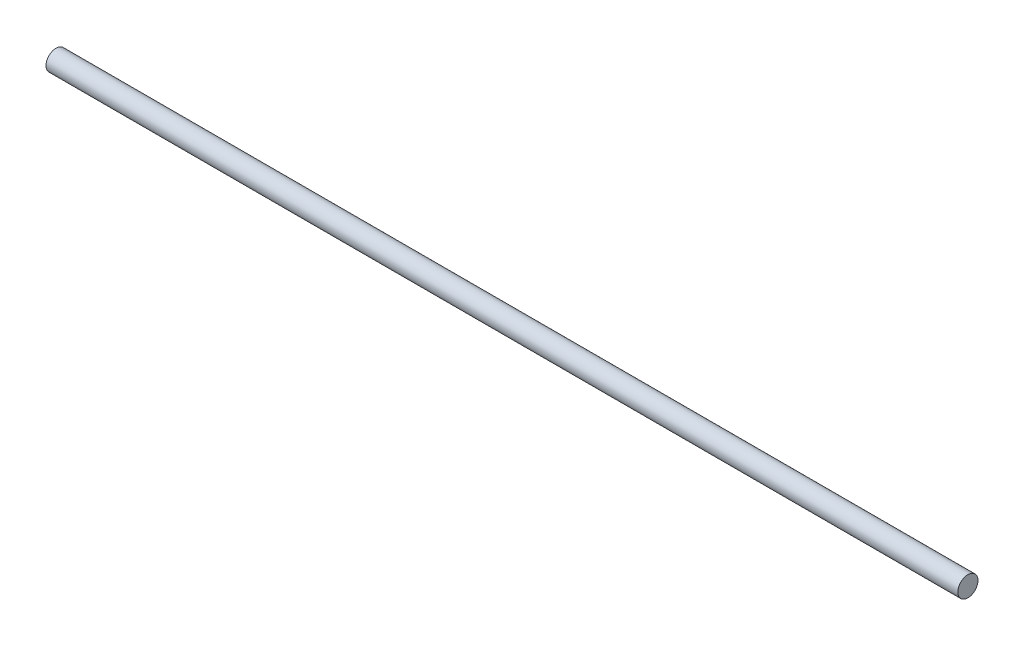
SolidWorks part; units mm, degrees
material "Aço inoxidável fundido"
ref_plane "Plano frontal" through (0, 0, 0) normal (0, 0, 1) x (1, 0, 0)
ref_plane "Plano superior" through (0, 0, 0) normal (0, 1, 0) x (1, 0, 0)
ref_plane "Plano direito" through (0, 0, 0) normal (1, 0, 0) x (0, 0, -1)
sketch "Esboço1" plane through (0, 0, 0) normal (1, 0, 0) x (0, 0, -1)
  circle A0 centre (0, 0) radius 4
  dimension "D1" = 8
extrude "Ressalto-extrusão1" add sketch "Esboço1" along normal mid plane 362
